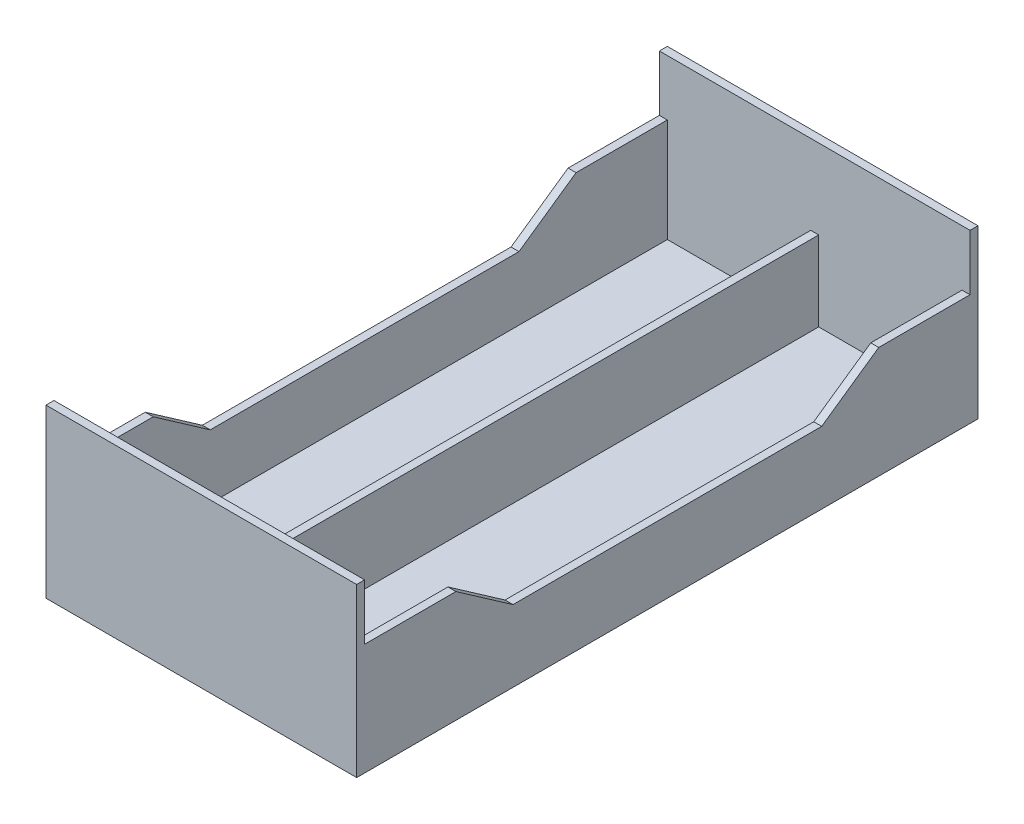
SolidWorks part; units mm, degrees
ref_plane "Front Plane" through (0, 0, 0) normal (0, 0, 1) x (1, 0, 0)
ref_plane "Top Plane" through (0, 0, 0) normal (0, 1, 0) x (1, 0, 0)
ref_plane "Right Plane" through (0, 0, 0) normal (1, 0, 0) x (0, 0, -1)
sketch "Sketch1" plane through (0, 0, 0) normal (1, 0, 0) x (0, 0, -1)
  line L0 (-39, 10.5) -> (-38, 10.5)
  line L1 (26.5396, 3.5) -> (19.3769, -1.5)
  line L2 (-39, 10.5) -> (-39, -10.5)
  line L3 (-39, -10.5) -> (39, -10.5)
  line L4 (39, 10.5) -> (39, -10.5)
  line L5 (-39, 10.5) -> (39, -10.5) construction
  line L6 (-39, -10.5) -> (39, 10.5) construction
  line L7 (-38, 10.5) -> (-38, 3.5)
  line L8 (-38, 3.5) -> (-26.5396, 3.5)
  line L9 (-26.5396, 3.5) -> (-19.3769, -1.5)
  line L10 (-19.3769, -1.5) -> (19.3769, -1.5)
  line L11 (0, -1.5) -> (0, -7.0472) construction
  line L12 (38, 3.5) -> (26.5396, 3.5)
  line L13 (38, 10.5) -> (38, 3.5)
  line L14 (39, 10.5) -> (38, 10.5)
  point P0 (0, 0)
  dimension "D1" = 21
  dimension "D2" = 78
  dimension "D3" = 1
  dimension "D4" = 7
  dimension "D5" = 5
extrude "Boss-Extrude1" add sketch "Sketch1" along normal blind 1
sketch "Sketch2" plane through (1, 0, 0) normal (1, 0, 0) x (0, 0, -1)
  line L0 (-38, 10.5) -> (-38, -9.5)
  line L1 (38, 10.5) -> (38, -9.5)
  line L2 (38, -9.5) -> (-38, -9.5)
  line L12 (39, -10.5) -> (39, 10.5)
  line L13 (39, 10.5) -> (38, 10.5)
  line L14 (38, 10.5) -> (38, 3.5)
  line L15 (38, 3.5) -> (26.5396, 3.5)
  line L16 (26.5396, 3.5) -> (19.3769, -1.5)
  line L17 (19.3769, -1.5) -> (-19.3769, -1.5)
  line L18 (-19.3769, -1.5) -> (-26.5396, 3.5)
  line L19 (-26.5396, 3.5) -> (-38, 3.5)
  line L20 (-38, 3.5) -> (-38, 10.5)
  line L21 (-38, 10.5) -> (-39, 10.5)
  line L22 (-39, 10.5) -> (-39, -10.5)
  line L23 (-39, -10.5) -> (39, -10.5)
  line L24 (39, -10.5) -> (39, 10.5)
  line L25 (39, 10.5) -> (38, 10.5)
  line L33 (-38, 10.5) -> (-39, 10.5)
  line L34 (-39, 10.5) -> (-39, -10.5)
  line L35 (-39, -10.5) -> (39, -10.5)
  dimension "D2" = 20
  dimension "D3" = 20
  dimension "D1" = 0
extrude "Boss-Extrude2" add sketch "Sketch2" along normal blind 37
ref_plane "Plane1" through (19.5, 0, 0) normal (1, 0, 0) x (0, 0, -1)
mirror "Mirror1" about plane through (19.5, 0, 0) normal (1, 0, 0) of "Boss-Extrude1"
sketch "Sketch4" plane through (19.5, 0, 0) normal (1, 0, 0) x (0, 0, -1)
  line L0 (-38, -9.5) -> (-38, 0.5)
  line L1 (-38, 0.5) -> (38, 0.5)
  line L2 (38, 0.5) -> (38, -9.5)
  line L8 (-38, 3.5) -> (-38, -9.5)
  line L9 (-38, -9.5) -> (38, -9.5)
  line L10 (38, -9.5) -> (38, 3.5)
  line L11 (38, 3.5) -> (26.5396, 3.5)
  line L12 (26.5396, 3.5) -> (19.3769, -1.5)
  line L13 (19.3769, -1.5) -> (-19.3769, -1.5)
  line L14 (-19.3769, -1.5) -> (-26.5396, 3.5)
  line L15 (-26.5396, 3.5) -> (-38, 3.5)
  line L17 (-38, -9.5) -> (38, -9.5)
  dimension "D2" = 10
  dimension "D1" = 0
extrude "Boss-Extrude3" add sketch "Sketch4" along normal mid plane 1
